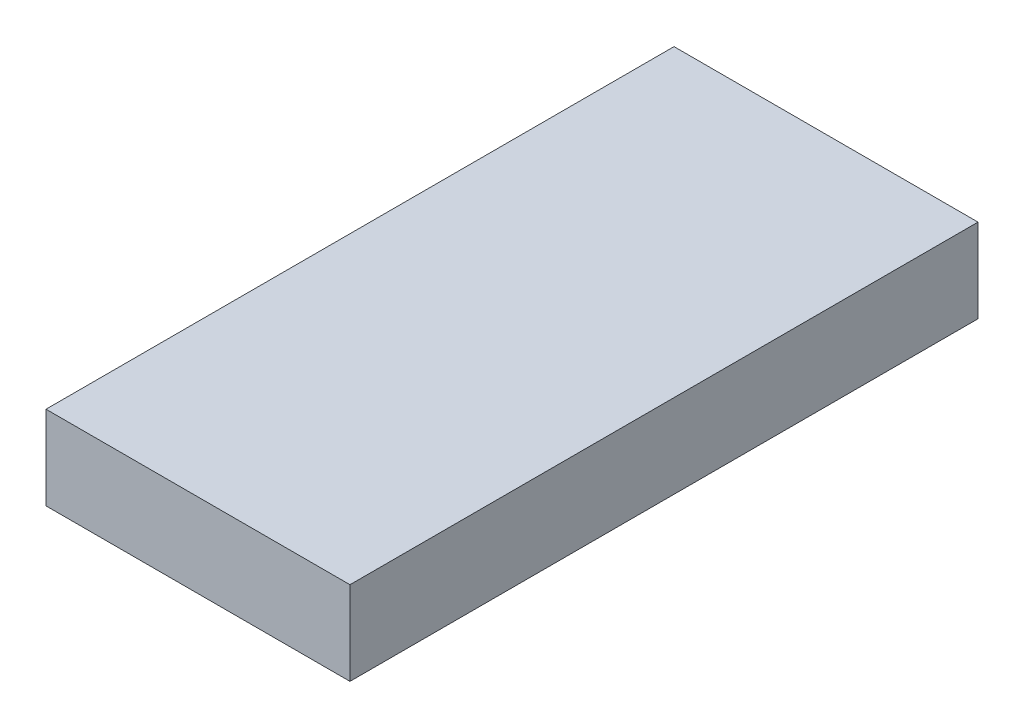
SolidWorks part; units mm, degrees
ref_plane "Front Plane" through (0, 0, 0) normal (0, 0, 1) x (1, 0, 0)
ref_plane "Top Plane" through (0, 0, 0) normal (0, 1, 0) x (1, 0, 0)
ref_plane "Right Plane" through (0, 0, 0) normal (1, 0, 0) x (0, 0, -1)
sketch "Sketch1" plane through (0, 0, 0) normal (0, 1, 0) x (1, 0, 0)
  line L1 (-31.9287, 126.0535) -> (40.6713, 126.0535)
  line L2 (-31.9287, 126.0535) -> (-31.9287, -23.9465)
  line L3 (-31.9287, -23.9465) -> (40.6713, -23.9465)
  line L4 (40.6713, 126.0535) -> (40.6713, -23.9465)
extrude "Boss-Extrude1" add sketch "Sketch1" along normal blind 20
